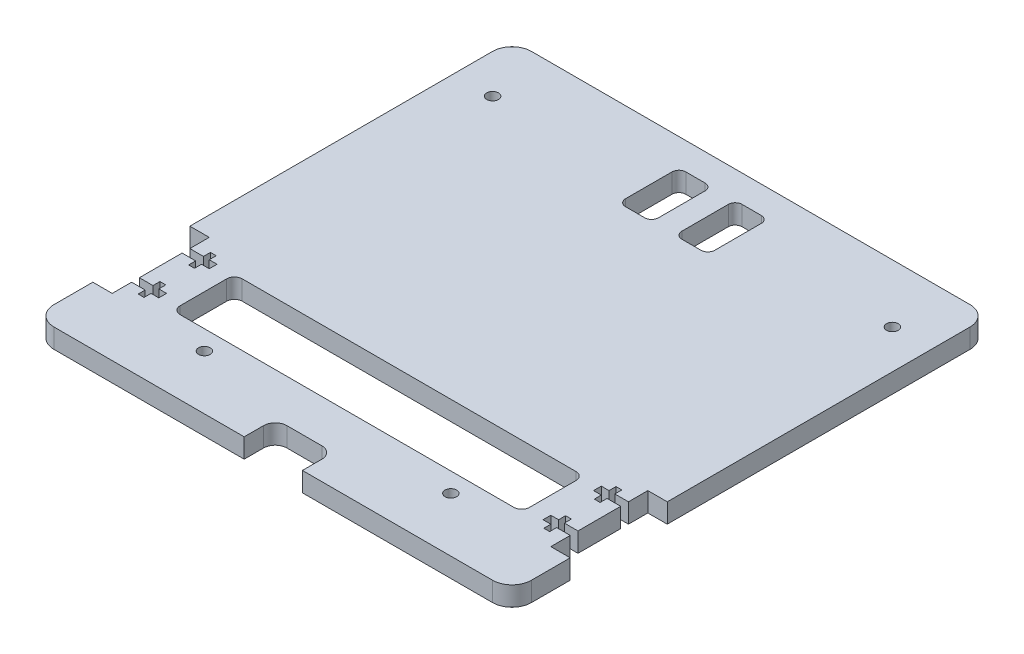
SolidWorks part; units mm, degrees
material "Acrílico (médio-alto impacto)"
ref_plane "Plano frontal" through (0, 0, 0) normal (0, 0, 1) x (1, 0, 0)
ref_plane "Plano superior" through (0, 0, 0) normal (0, 1, 0) x (1, 0, 0)
ref_plane "Plano direito" through (0, 0, 0) normal (1, 0, 0) x (0, 0, -1)
sketch "Esboço1" plane through (0, 0, 0) normal (0, 1, 0) x (1, 0, 0)
  line L1 (-56.5, -61.5) -> (56.5, -61.5)
  line L2 (-61.5, -56.5) -> (-61.5, 56.5)
  line L3 (-56.5, 61.5) -> (56.5, 61.5)
  line L4 (61.5, -56.5) -> (61.5, 56.5)
  arc A0 (61.5, -56.5) -> (56.5, -61.5) centre (56.5, -56.5) cw
  arc A1 (-56.5, -61.5) -> (-61.5, -56.5) centre (-56.5, -56.5) cw
  arc A2 (61.5, 56.5) -> (56.5, 61.5) centre (56.5, 56.5) ccw
  arc A3 (-56.5, 61.5) -> (-61.5, 56.5) centre (-56.5, 56.5) ccw
  point P0 (0, 0)
  dimension "D1" = 5
extrude "Ressalto-extrusão1" add sketch "Esboço1" along normal blind 5
sketch "Esboço2" plane through (0, 5, 0) normal (0, 1, 0) x (1, 0, 0)
  line L0 (61.5, -56.5) -> (61.5, 56.5) construction
  line L1 (-61.5, 56.5) -> (-61.5, -56.5) construction
  line L2 (56.5, 61.5) -> (-56.5, 61.5) construction
  line L11 (-4.7656, 54.5) -> (-9.7331, 54.5)
  line L12 (-2.9988, 52.7331) -> (-2.9988, 40.7331)
  line L13 (-4.7656, 38.9662) -> (-9.7331, 38.9662)
  line L14 (-11.5, 52.7331) -> (-11.5, 40.7331)
  line L15 (4.7681, 38.9662) -> (9.7331, 38.9662)
  line L16 (3.0012, 40.7331) -> (3.0012, 52.7331)
  line L17 (4.7681, 54.5) -> (9.7331, 54.5)
  line L18 (11.5, 40.7331) -> (11.5, 52.7331)
  arc A0 (-4.7656, 38.9662) -> (-2.9988, 40.7331) centre (-4.7656, 40.7331) ccw
  arc A1 (-9.7331, 38.9662) -> (-11.5, 40.7331) centre (-9.7331, 40.7331) cw
  arc A2 (-11.5, 52.7331) -> (-9.7331, 54.5) centre (-9.7331, 52.7331) cw
  arc A3 (-4.7656, 54.5) -> (-2.9988, 52.7331) centre (-4.7656, 52.7331) cw
  arc A8 (3.0012, 52.7331) -> (4.7681, 54.5) centre (4.7681, 52.7331) cw
  arc A9 (4.7681, 38.9662) -> (3.0012, 40.7331) centre (4.7681, 40.7331) cw
  arc A10 (9.7331, 38.9662) -> (11.5, 40.7331) centre (9.7331, 40.7331) ccw
  arc A11 (11.5, 52.7331) -> (9.7331, 54.5) centre (9.7331, 52.7331) ccw
  point P43 (-7.2494, 54.5)
  dimension "D1" = 50
  dimension "D2" = 50
  dimension "D3" = 6
  dimension "D6" = 1.7669
  dimension "D4" = 4.965
  dimension "D7" = 7
  dimension "D8" = 7
extrude "Corte-extrusão1" cut sketch "Esboço2" against normal blind 5
sketch "Esboço3" plane through (0, 5, 0) normal (0, 1, 0) x (1, 0, 0)
  line L0 (-61.5, 56.5) -> (-61.5, -56.5) construction
  line L1 (-61.5, -46.5) -> (-56.5, -46.5)
  line L2 (-61.5, -46.5) -> (-61.5, -21.5)
  line L3 (-61.5, -21.5) -> (-56.5, -21.5)
  line L4 (-56.5, -46.5) -> (-56.5, -21.5)
  line L5 (-56.5, -61.5) -> (56.5, -61.5) construction
  line L6 (61.5, -56.5) -> (61.5, 56.5) construction
  line L7 (61.5, -46.5) -> (56.5, -46.5)
  line L8 (61.5, -46.5) -> (61.5, -21.5)
  line L9 (61.5, -21.5) -> (56.5, -21.5)
  line L10 (56.5, -46.5) -> (56.5, -21.5)
  line L11 (-56.5, -61.5) -> (56.5, -61.5) construction
  dimension "D1" = 15
  dimension "D2" = 15
extrude "Corte-extrusão3" cut sketch "Esboço3" against normal blind 5
sketch "Esboço4" plane through (0, 5, 0) normal (0, 1, 0) x (1, 0, 0)
  line L0 (56.5, -21.5) -> (56.5, -46.5) construction
  line L1 (56.5, -41.5) -> (53, -41.5)
  line L2 (56.5, -41.5) -> (56.5, -39.5)
  line L3 (56.5, -39.5) -> (53, -39.5)
  line L4 (61.5, -21.5) -> (56.5, -21.5) construction
  line L5 (-56.5, -61.5) -> (56.5, -61.5) construction
  line L6 (53, -37.7) -> (51.5, -37.7)
  line L7 (53, -37.7) -> (53, -39.5)
  line L8 (53, -43.3) -> (51.5, -43.3)
  line L9 (51.5, -37.7) -> (51.5, -39.5)
  line L10 (53, -41.5) -> (53, -43.3)
  line L11 (56.5, -26.5) -> (53, -26.5)
  line L12 (51.5, -39.5) -> (49.5, -39.5)
  line L13 (53, -26.5) -> (53, -24.7)
  line L14 (51.5, -41.5) -> (49.5, -41.5)
  line L15 (49.5, -39.5) -> (49.5, -41.5)
  line L16 (51.5, -41.5) -> (51.5, -43.3)
  line L17 (56.5, -26.5) -> (56.5, -28.5)
  line L18 (56.5, -28.5) -> (53, -28.5)
  line L20 (51.5, -26.5) -> (51.5, -24.7)
  line L21 (51.5, -30.3) -> (53, -30.3)
  line L22 (51.5, -30.3) -> (51.5, -28.5)
  line L23 (51.5, -24.7) -> (53, -24.7)
  line L24 (53, -30.3) -> (53, -28.5)
  line L25 (51.5, -28.5) -> (49.5, -28.5)
  line L27 (51.5, -26.5) -> (49.5, -26.5)
  line L28 (49.5, -28.5) -> (49.5, -26.5)
  dimension "D1" = 20
  dimension "D2" = 1.8
  dimension "D3" = 1.8
  dimension "D4" = 3.5
  dimension "D5" = 5
  dimension "D6" = 1.8
  dimension "D7" = 1.8
extrude "Corte-extrusão4" cut sketch "Esboço4" against normal blind 10
mirror "Espelhar1" about plane through (0, 0, 0) normal (1, 0, 0) of "Corte-extrusão4"
sketch "Esboço5" plane through (0, 5, 0) normal (0, 1, 0) x (1, 0, 0)
  line L0 (-61.5, -46.5) -> (-61.5, -56.5) construction
  line L1 (43, -42.5) -> (-43, -42.5)
  line L2 (45, -40.5) -> (45, -28.5)
  line L3 (43, -26.5) -> (-43, -26.5)
  line L4 (-45, -40.5) -> (-45, -28.5)
  line L5 (61.5, -56.5) -> (61.5, -46.5) construction
  line L6 (-56.5, -61.5) -> (56.5, -61.5) construction
  arc A0 (45, -40.5) -> (43, -42.5) centre (43, -40.5) cw
  arc A1 (45, -28.5) -> (43, -26.5) centre (43, -28.5) ccw
  arc A2 (-43, -26.5) -> (-45, -28.5) centre (-43, -28.5) ccw
  arc A3 (-43, -42.5) -> (-45, -40.5) centre (-43, -40.5) cw
  point P14 (-61.5, -51.5)
  point P17 (61.5, -51.5)
  dimension "D1" = 2
  dimension "D2" = 16.5
  dimension "D3" = 16.5
  dimension "D4" = 19
extrude "Corte-extrusão5" cut sketch "Esboço5" against normal blind 5
sketch "Esboço6" plane through (0, 5, 0) normal (0, 1, 0) x (1, 0, 0)
  line L0 (56.5, 61.5) -> (-56.5, 61.5) construction
  line L1 (-61.5, 56.5) -> (-61.5, -21.5) construction
  line L2 (61.5, -21.5) -> (61.5, 56.5) construction
  line L3 (-56.5, -61.5) -> (56.5, -61.5) construction
  line L4 (-56.5, -61.5) -> (56.5, -61.5) construction
  line L5 (61.5, -56.5) -> (61.5, -46.5) construction
  line L6 (-61.5, -46.5) -> (-61.5, -56.5) construction
  circle A0 centre (-51.5, 46.5) radius 1.5
  circle A1 centre (51.5, 46.5) radius 1.5
  circle A2 centre (31.75, -47.5) radius 1.5
  circle A3 centre (-31.75, -47.5) radius 1.5
  point P17 (61.5, -51.5)
  dimension "D1" = 15
  dimension "D2" = 10
  dimension "D3" = 15
  dimension "D4" = 10
  dimension "D5" = 14
  dimension "D6" = 29.75
  dimension "D7" = 29.75
  dimension "D8" = 14
extrude "Corte-extrusão6" cut sketch "Esboço6" against normal blind 20
sketch "Esboço7" plane through (0, 0, 0) normal (0, -1, 0) x (1, 0, 0)
  line L0 (-56.5, 61.5) -> (56.5, 61.5) construction
  line L1 (7.5, 61.5) -> (-7.5, 61.5)
  line L2 (7.5, 61.5) -> (7.5, 56.5)
  line L3 (4.5, 53.5) -> (-4.5, 53.5)
  line L4 (-7.5, 61.5) -> (-7.5, 56.5)
  line L5 (61.5, 56.5) -> (61.5, 46.5) construction
  line L6 (-61.5, 46.5) -> (-61.5, 56.5) construction
  arc A0 (7.5, 56.5) -> (4.5, 53.5) centre (4.5, 56.5) cw
  arc A1 (-4.5, 53.5) -> (-7.5, 56.5) centre (-4.5, 56.5) cw
  dimension "D3" = 3
  dimension "D1" = 54
  dimension "D2" = 54
extrude "Corte-extrusão7" cut sketch "Esboço7" against normal blind 10
